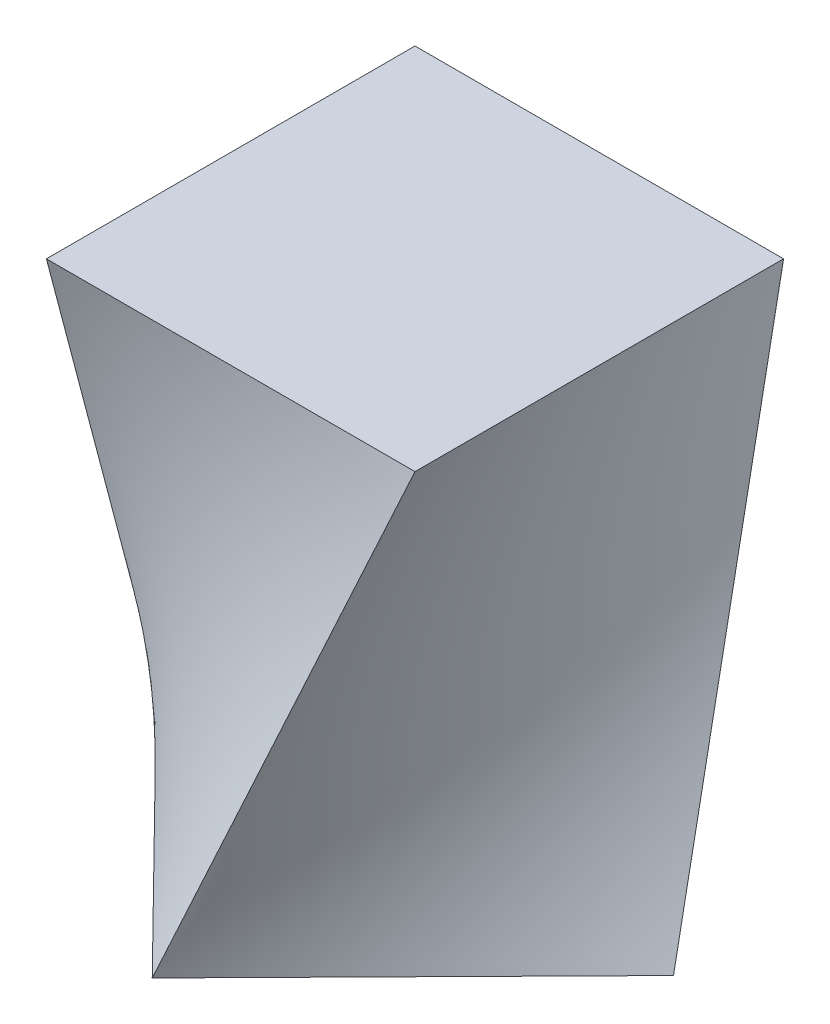
SolidWorks part; units mm, degrees
ref_plane "정면" through (0, 0, 0) normal (0, 0, 1) x (1, 0, 0)
ref_plane "윗면" through (0, 0, 0) normal (0, 1, 0) x (1, 0, 0)
ref_plane "우측면" through (0, 0, 0) normal (1, 0, 0) x (0, 0, -1)
sketch "Sketch1" plane through (0, 0, 0) normal (0, 1, 0) x (1, 0, 0)
  line L0 (0, -42.7727) -> (0, 42.7727) construction
  line L1 (-42.0772, 0) -> (0, -42.7727)
  line L2 (-42.0772, 0) -> (0, 42.7727)
  line L3 (0, -42.7727) -> (42.0772, 0)
  line L4 (0, 42.7727) -> (42.0772, 0)
  point P3 (0, 0)
  point P4 (0, 0)
  dimension "D1" = 60
ref_plane "Plane1" through (0, 80, 0) normal (0, 1, 0) x (1, 0, 0)
sketch "Sketch2" plane through (0, 80, 0) normal (0, 1, 0) x (1, 0, 0)
  line L1 (-30, -30) -> (30, -30)
  line L2 (-30, -30) -> (-30, 30)
  line L3 (-30, 30) -> (30, 30)
  line L4 (30, -30) -> (30, 30)
  line L5 (-30, -30) -> (30, 30) construction
  line L6 (-30, 30) -> (30, -30) construction
  point P0 (0, 0)
  dimension "D1" = 60
  dimension "D2" = 60
loft "Loft1" add profiles "Sketch1", "Sketch2"
